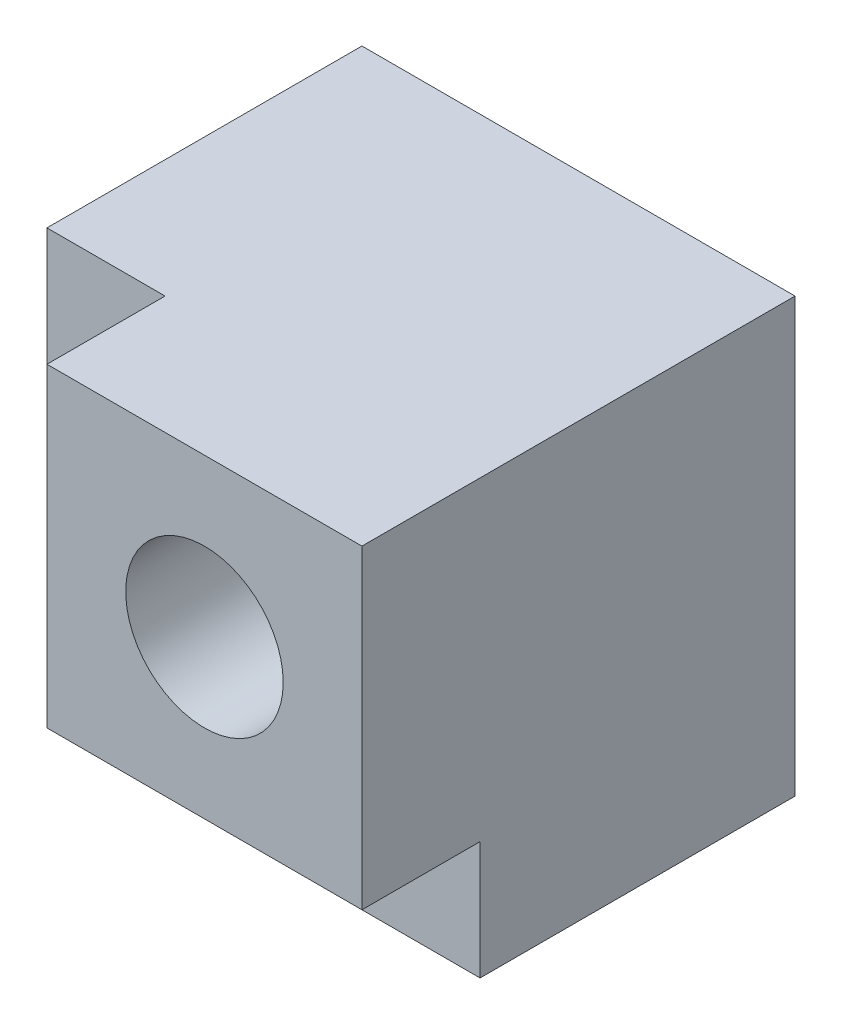
SolidWorks part; units mm, degrees
ref_plane "Plan de face" through (0, 0, 0) normal (0, 0, 1) x (1, 0, 0)
ref_plane "Plan de dessus" through (0, 0, 0) normal (0, 1, 0) x (1, 0, 0)
ref_plane "Plan de droite" through (0, 0, 0) normal (1, 0, 0) x (0, 0, -1)
sketch "Esquisse2" plane through (0, 0, 0) normal (0, 1, 0) x (1, 0, 0)
  line L1 (-40, 40) -> (40, 40)
  line L2 (-40, 40) -> (-40, -40)
  line L3 (-40, -40) -> (40, -40)
  line L4 (40, 40) -> (40, -40)
  line L5 (-40, 40) -> (40, -40) construction
  line L6 (-40, -40) -> (40, 40) construction
  point P0 (0, 0)
  dimension "D1" = 80
  dimension "D2" = 80
extrude "Boss.-Extru.1" add sketch "Esquisse2" along normal blind 80
sketch "Esquisse5" plane through (-40, 0, 0) normal (-1, 0, 0) x (0, 0, 1)
  line L1 (-40, 80) -> (40, 80)
  line L2 (-40, 80) -> (-40, 0)
  line L3 (-40, 0) -> (40, 0)
  line L4 (40, 80) -> (40, 0)
extrude "Boss.-Extru.2" add sketch "Esquisse5" along normal blind 30
sketch "Esquisse6" plane through (0, 0, 40) normal (0, 0, 1) x (1, 0, 0)
  line L0 (40, 40) -> (-40, 40) construction
  line L1 (40, 80) -> (40, 0) construction
  line L2 (-70, 0) -> (40, 0) construction
  line L3 (40, 80) -> (-40, 80)
  line L4 (40, 80) -> (40, 0)
  line L5 (40, 0) -> (-40, 0)
  line L6 (-40, 80) -> (-40, 0)
  dimension "D1" = 80
extrude "Boss.-Extru.3" add sketch "Esquisse6" along normal blind 30
sketch "Esquisse7" plane through (0, 0, 0) normal (0, -1, 0) x (1, 0, 0)
  line L1 (-40, 40) -> (40, 40)
  line L2 (-40, 40) -> (-40, -40)
  line L3 (-40, -40) -> (40, -40)
  line L4 (40, 40) -> (40, -40)
extrude "Boss.-Extru.4" add sketch "Esquisse7" along normal blind 30
sketch "Esquisse8" plane through (-70, 0, 0) normal (-1, 0, 0) x (0, 0, 1)
  line L0 (0, 0) -> (0, 80) construction
  line L1 (-40, 0) -> (40, 0) construction
  line L2 (40, 80) -> (-40, 80) construction
  circle A0 centre (0, 40) radius 20
  dimension "D1" = 40
extrude "Enlèv. mat.-Extru.1" cut sketch "Esquisse8" against normal blind 45
sketch "Esquisse9" plane through (0, 0, 70) normal (0, 0, 1) x (1, 0, 0)
  line L0 (0, 0) -> (0, 80) construction
  line L1 (-40, 0) -> (40, 0) construction
  line L2 (40, 80) -> (-40, 80) construction
  circle A0 centre (0, 40) radius 20
  dimension "D1" = 40
extrude "Enlèv. mat.-Extru.2" cut sketch "Esquisse9" against normal blind 45
sketch "Esquisse10" plane through (0, -30, 0) normal (0, -1, 0) x (1, 0, 0)
  line L0 (40, 0) -> (-40, 0) construction
  line L1 (40, -40) -> (40, 40) construction
  line L2 (-40, 40) -> (-40, -40) construction
  circle A0 centre (0, 0) radius 20
  dimension "D1" = 40
extrude "Enlèv. mat.-Extru.3" cut sketch "Esquisse10" against normal blind 45
equation "\"40u\"=50.2739"
